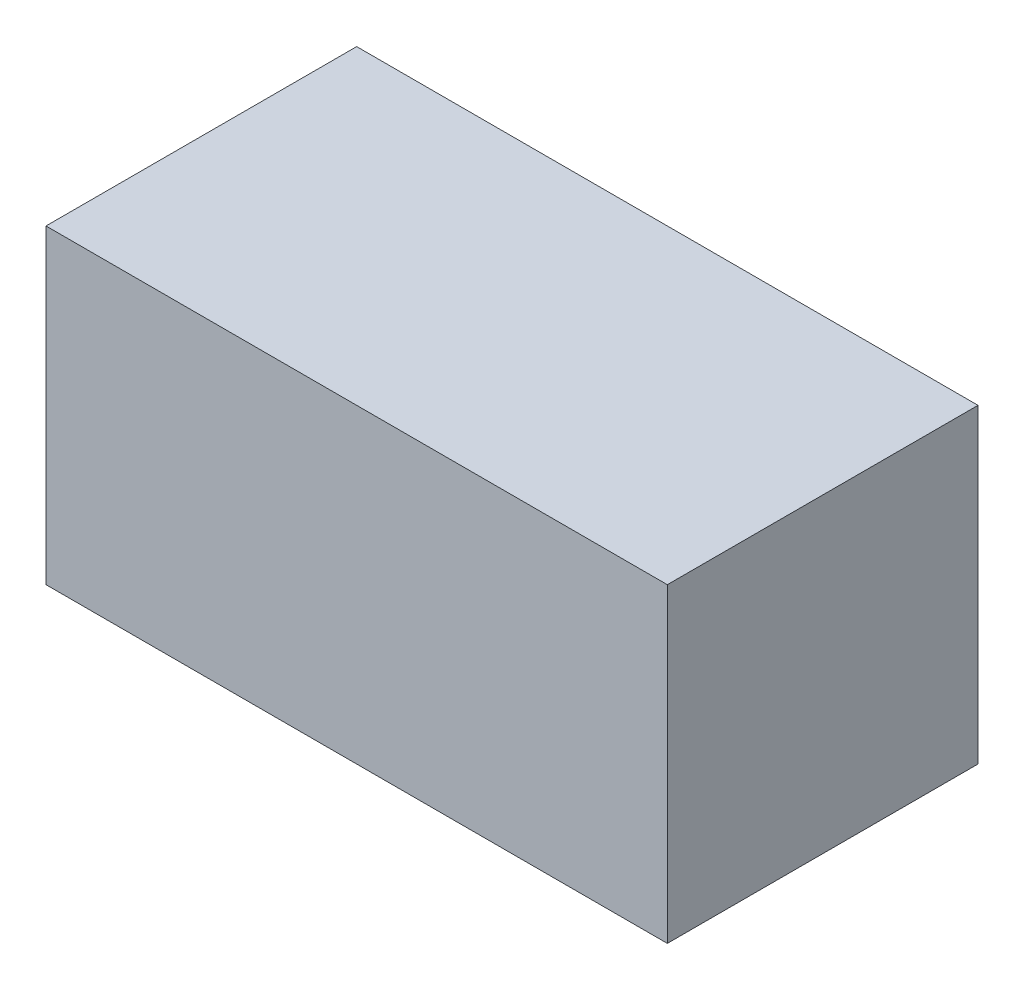
SolidWorks part; units mm, degrees
ref_plane "Front Plane" through (0, 0, 0) normal (0, 0, 1) x (1, 0, 0)
ref_plane "Top Plane" through (0, 0, 0) normal (0, 1, 0) x (1, 0, 0)
ref_plane "Right Plane" through (0, 0, 0) normal (1, 0, 0) x (0, 0, -1)
sketch "Sketch1" plane through (0, 0, 0) normal (0, 0, 1) x (1, 0, 0)
  line L1 (0, 0) -> (10, 0)
  line L2 (0, 0) -> (0, 5)
  line L3 (0, 5) -> (10, 5)
  line L4 (10, 0) -> (10, 5)
  dimension "D1" = 10
  dimension "D2" = 5
extrude "Boss-Extrude1" add sketch "Sketch1" along normal blind 5
